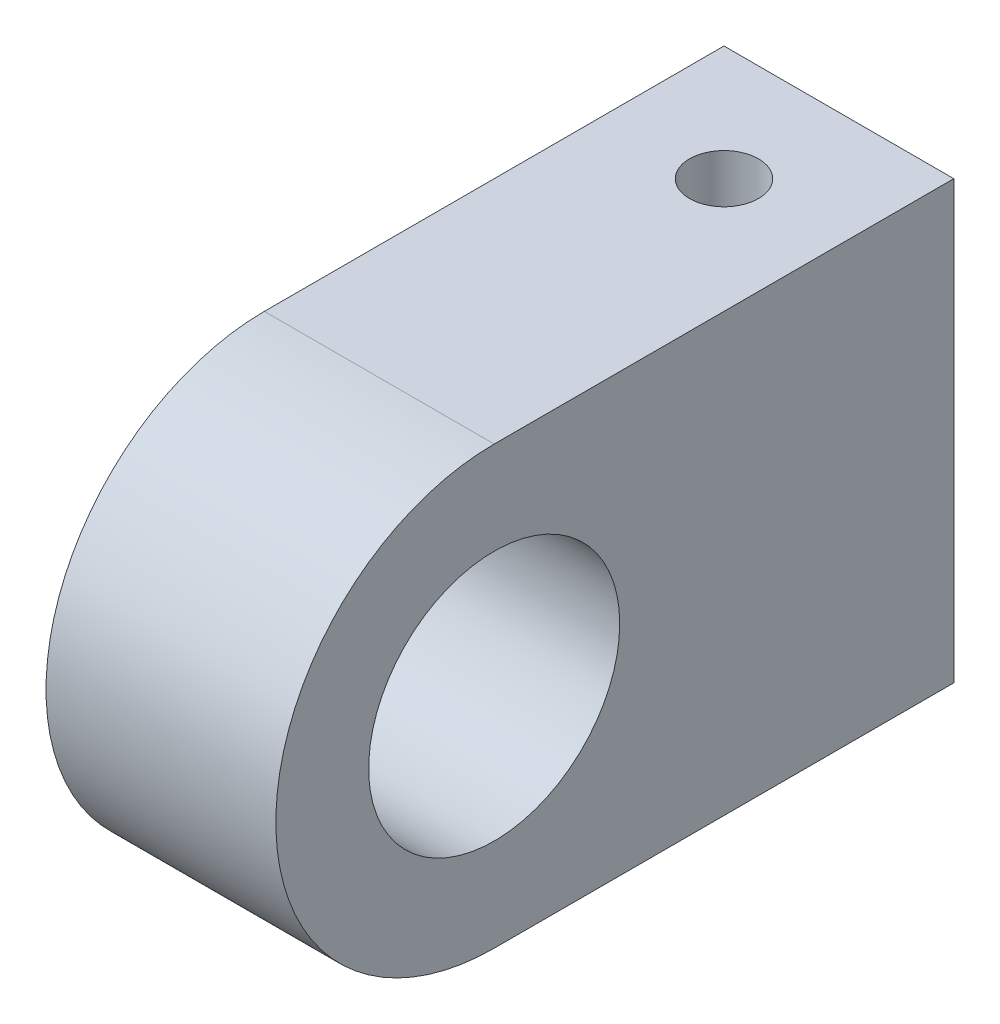
SolidWorks part; units mm, degrees
ref_plane "前视基准面" through (0, 0, 0) normal (0, 0, 1) x (1, 0, 0)
ref_plane "上视基准面" through (0, 0, 0) normal (0, 1, 0) x (1, 0, 0)
ref_plane "右视基准面" through (0, 0, 0) normal (1, 0, 0) x (0, 0, -1)
sketch "草图1" plane through (0, 0, 0) normal (1, 0, 0) x (0, 0, -1)
  line L0 (0, 9.5) -> (20, 9.5)
  line L1 (20, 9.5) -> (20, -9.5)
  line L2 (20, -9.5) -> (0, -9.5)
  circle A0 centre (0, 0) radius 5.4628
  arc A1 (-9.5, 0) -> (0, 9.5) centre (0, 0) cw
  arc A2 (-9.5, 0) -> (0, -9.5) centre (0, 0) ccw
  dimension "D1" = 20
  dimension "D2" = 9.5
extrude "凸台-拉伸1" add sketch "草图1" along normal blind 10
sketch "草图2" plane through (0, 9.5, 0) normal (0, 1, 0) x (1, 0, 0)
  line L0 (0, 20) -> (10, 10) construction
  line L1 (0, 20) -> (0, 0) construction
  line L2 (10, 20) -> (10, 0) construction
  circle A0 centre (5, 15) radius 1.5
extrude "切除-拉伸1" cut sketch "草图2" against normal through all
